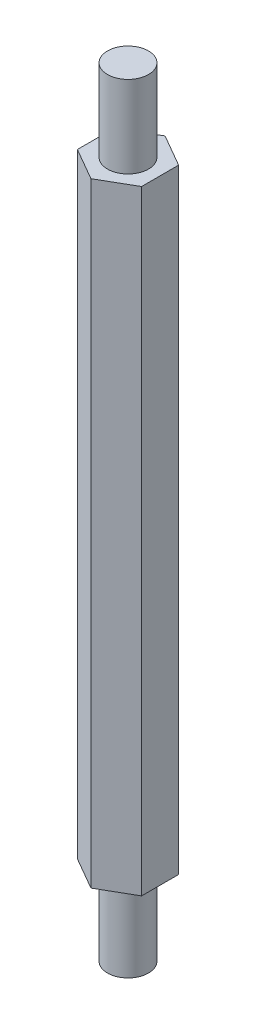
SolidWorks part; units mm, degrees
ref_plane "Front Plane" through (0, 0, 0) normal (0, 0, 1) x (1, 0, 0)
ref_plane "Top Plane" through (0, 0, 0) normal (0, 1, 0) x (1, 0, 0)
ref_plane "Right Plane" through (0, 0, 0) normal (1, 0, 0) x (0, 0, -1)
sketch "Sketch1" plane through (0, 0, 0) normal (0, 1, 0) x (1, 0, 0)
  line L1 (0, 2.7135) -> (-2.35, 1.3568)
  line L2 (-2.35, 1.3568) -> (-2.35, -1.3568)
  line L3 (-2.35, -1.3568) -> (0, -2.7135)
  line L4 (0, -2.7135) -> (2.35, -1.3568)
  line L5 (2.35, -1.3568) -> (2.35, 1.3568)
  line L6 (2.35, 1.3568) -> (0, 2.7135)
  circle A0 centre (0, 0) radius 2.35 construction
  dimension "D1" = 4.7
extrude "Boss-Extrude1" add sketch "Sketch1" along normal blind 45
sketch "Sketch2" plane through (0, 45, 0) normal (0, 1, 0) x (1, 0, 0)
  circle A0 centre (0, 0) radius 1.5
  dimension "D1" = 3
extrude "Boss-Extrude2" add sketch "Sketch2" along normal blind 6
sketch "Sketch5" plane through (0, 0, 0) normal (0, -1, 0) x (1, 0, 0)
  circle A0 centre (0, 0) radius 1.5
  dimension "D1" = 3
extrude "Boss-Extrude3" add sketch "Sketch5" along normal blind 6 contours A0
